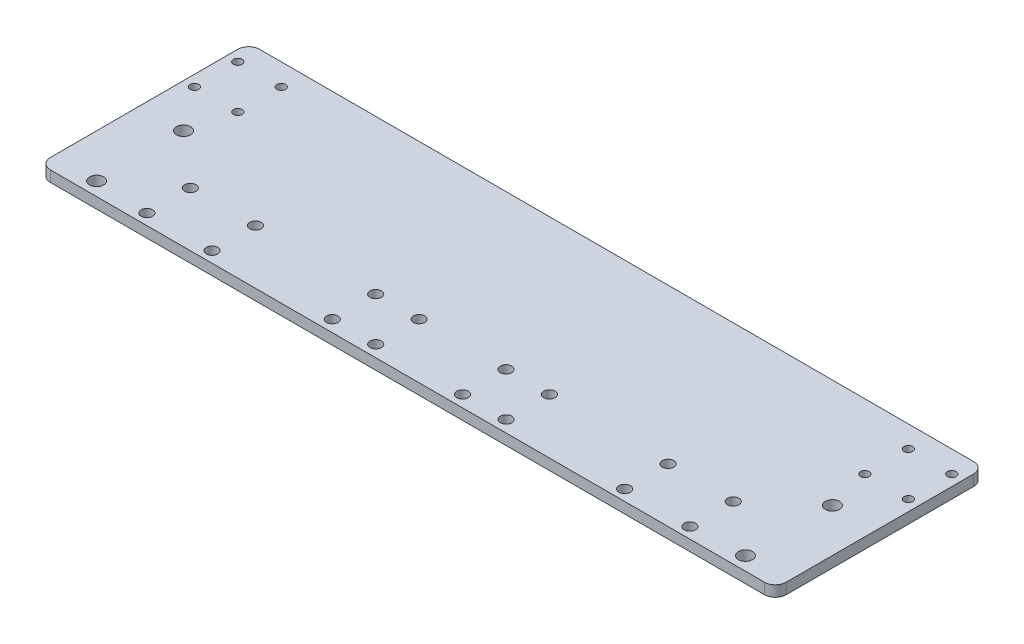
SolidWorks part; units mm, degrees
ref_plane "前视基准面" through (0, 0, 0) normal (0, 0, 1) x (1, 0, 0)
ref_plane "上视基准面" through (0, 0, 0) normal (0, 1, 0) x (1, 0, 0)
ref_plane "右视基准面" through (0, 0, 0) normal (1, 0, 0) x (0, 0, -1)
sketch "草图1" plane through (0, 0, 0) normal (0, 1, 0) x (1, 0, 0)
  line L0 (43.3669, 50.3186) -> (43.3669, 19.3186)
  line L2 (-227.6331, 19.3186) -> (-227.6331, -18.6814)
  line L3 (-223.6331, -22.6814) -> (39.3669, -22.6814)
  line L4 (43.3669, 19.3186) -> (43.3669, -18.6814)
  line L5 (39.3669, 54.3186) -> (-223.6331, 54.3186)
  line L6 (-227.6331, 50.3186) -> (-227.6331, 19.3186)
  circle A0 centre (-211.6331, 14.3186) radius 2.6
  arc A1 (43.3669, -18.6814) -> (39.3669, -22.6814) centre (39.3669, -18.6814) cw
  circle A2 centre (-211.6331, -17.6814) radius 2.6
  arc A3 (-227.6331, -18.6814) -> (-223.6331, -22.6814) centre (-223.6331, -18.6814) ccw
  arc A4 (39.3669, 54.3186) -> (43.3669, 50.3186) centre (39.3669, 50.3186) cw
  circle A5 centre (27.3669, -17.6814) radius 2.6
  arc A6 (-223.6331, 54.3186) -> (-227.6331, 50.3186) centre (-223.6331, 50.3186) ccw
  circle A7 centre (-207.6331, 30.3186) radius 1.6
  circle A8 centre (-207.6331, 46.3186) radius 1.6
  circle A9 centre (-223.6331, 30.3186) radius 1.6
  circle A10 centre (-223.6331, 46.3186) radius 1.6
  circle A11 centre (27.3669, 14.3186) radius 2.6
  circle A12 centre (39.3669, 30.3186) radius 1.6
  circle A13 centre (23.3669, 30.3186) radius 1.6
  circle A14 centre (39.3669, 46.3186) radius 1.6
  circle A15 centre (23.3669, 46.3186) radius 1.6
  dimension "D1" = 3.2
  dimension "D4" = 23.3669
  dimension "D2" = 5.2
  dimension "D5" = 27.3669
  dimension "D6" = 271
  dimension "D3" = 4
  dimension "D7" = 43.3669
  dimension "D8" = 17.6814
  dimension "D13" = 19.3186
  dimension "D14" = 30.3186
  dimension "D15" = 46.3186
  dimension "D18" = 22.6814
  dimension "D9" = 207.6331
  dimension "D10" = 211.6331
  dimension "D12" = 14.3186
  dimension "D16" = 54.3186
extrude "凸台-拉伸1" add sketch "草图1" along normal blind 4
sketch "草图2" plane through (0, 4, 0) normal (0, 1, 0) x (1, 0, 0)
  line L0 (-92.1331, -22.6814) -> (-92.1331, 54.3186) construction
  line L1 (-223.6331, -22.6814) -> (39.3669, -22.6814) construction
  line L2 (39.3669, 54.3186) -> (-223.6331, 54.3186) construction
  line L3 (43.3669, 15.8186) -> (-227.6331, 15.8186) construction
  line L4 (43.3669, -18.6814) -> (43.3669, 50.3186) construction
  line L5 (-227.6331, 50.3186) -> (-227.6331, -18.6814) construction
  circle A8 centre (-124.1331, -2.3814) radius 2.1
  circle A9 centre (-124.1331, -18.3814) radius 2.1
  circle A10 centre (-108.1331, -18.3814) radius 2.1
  circle A11 centre (-108.1331, -2.3814) radius 2.1
  circle A12 centre (-76.1331, -2.3814) radius 2.1
  circle A13 centre (-76.1331, -18.3814) radius 2.1
  circle A14 centre (-60.1331, -18.3814) radius 2.1
  circle A15 centre (-60.1331, -2.3814) radius 2.1
  dimension "D1" = 4.2
  dimension "D2" = 16
  dimension "D3" = 16
  dimension "D6" = 4.3
extrude "切除-拉伸1" cut sketch "草图2" against normal blind 10
sketch "草图3" plane through (0, 4, 0) normal (0, 1, 0) x (1, 0, 0)
  line L0 (-223.6331, -22.6814) -> (39.3669, -22.6814) construction
  line L1 (-92.1331, -22.6814) -> (-92.1331, 54.3186) construction
  line L2 (39.3669, 54.3186) -> (-223.6331, 54.3186) construction
  circle A0 centre (7.8669, -18.6814) radius 2.1
  circle A1 centre (-16.1331, -18.6814) radius 2.1
  circle A2 centre (7.8669, -2.6814) radius 2.1
  circle A3 centre (-16.1331, -2.6814) radius 2.1
  circle A5 centre (-168.1331, -18.6814) radius 2.1
  circle A6 centre (-168.1331, -2.6814) radius 2.1
  circle A7 centre (-192.1331, -18.6814) radius 2.1
  circle A8 centre (-192.1331, -2.6814) radius 2.1
  dimension "D1" = 35.5
  dimension "D2" = 4.2
  dimension "D3" = 4
  dimension "D4" = 24
  dimension "D5" = 16
extrude "切除-拉伸2" cut sketch "草图3" against normal blind 10
